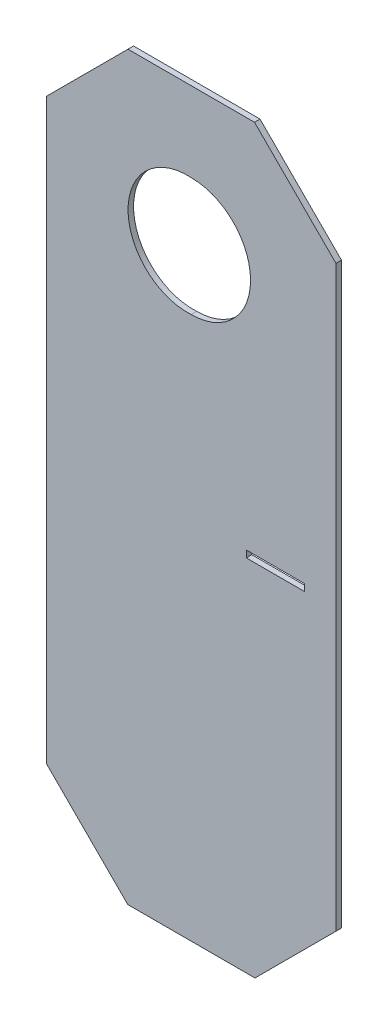
SolidWorks part; units mm, degrees
ref_plane "Спереди" through (0, 0, 0) normal (0, 0, 1) x (1, 0, 0)
ref_plane "Сверху" through (0, 0, 0) normal (0, 1, 0) x (1, 0, 0)
ref_plane "Справа" through (0, 0, 0) normal (1, 0, 0) x (0, 0, -1)
sketch "Эскиз1" plane through (0, 0, 0) normal (0, 0, 1) x (1, 0, 0)
  line L0 (105.0829, 581.7221) -> (45.979, 640.8259)
  line L1 (45.979, 640.8259) -> (-45.8132, 640.8259)
  line L2 (-45.8132, 640.8259) -> (-104.9171, 581.7221)
  line L3 (-104.9171, 581.7221) -> (-104.9171, 162.2129)
  line L4 (-104.9171, 162.2129) -> (-45.9732, 103.269)
  line L5 (-45.9732, 103.269) -> (46.3268, 103.269)
  line L6 (46.3268, 103.269) -> (105.0829, 162.0251)
  line L7 (105.0829, 162.0251) -> (105.0829, 581.7221)
  line L8 (0.0829, 640.8259) -> (0.0829, 703.4762) construction
  dimension "D1" = 105
  dimension "D2" = 105
extrude "Вытянуть1" add sketch "Эскиз1" along normal blind 4
sketch "Эскиз2" plane through (0, 0, 4) normal (0, 0, 1) x (1, 0, 0)
  line L0 (0.1173, 583.0246) -> (0.1173, 601.8308) construction
  arc A0 (0.1173, 497.0246) -> (0.1173, 583.0246) centre (0.1173, 540.0246) ccw
  arc A2 (0.1173, 583.0246) -> (0.1173, 497.0246) centre (-2.6747, 540.0246) ccw
extrude "Вырез-Вытянуть1" cut sketch "Эскиз2" against normal through all
sketch "Эскиз3" plane through (0, 0, 0) normal (0, 0, -1) x (-1, 0, 0)
  line L1 (-40.0192, 369.0881) -> (-82.1887, 369.0881)
  line L2 (-40.0192, 369.0881) -> (-40.0192, 364.0881)
  line L3 (-40.0192, 364.0881) -> (-82.1887, 364.0881)
  line L4 (-82.1887, 369.0881) -> (-82.1887, 364.0881)
extrude "Вырез-Вытянуть2" cut sketch "Эскиз3" against normal through all
